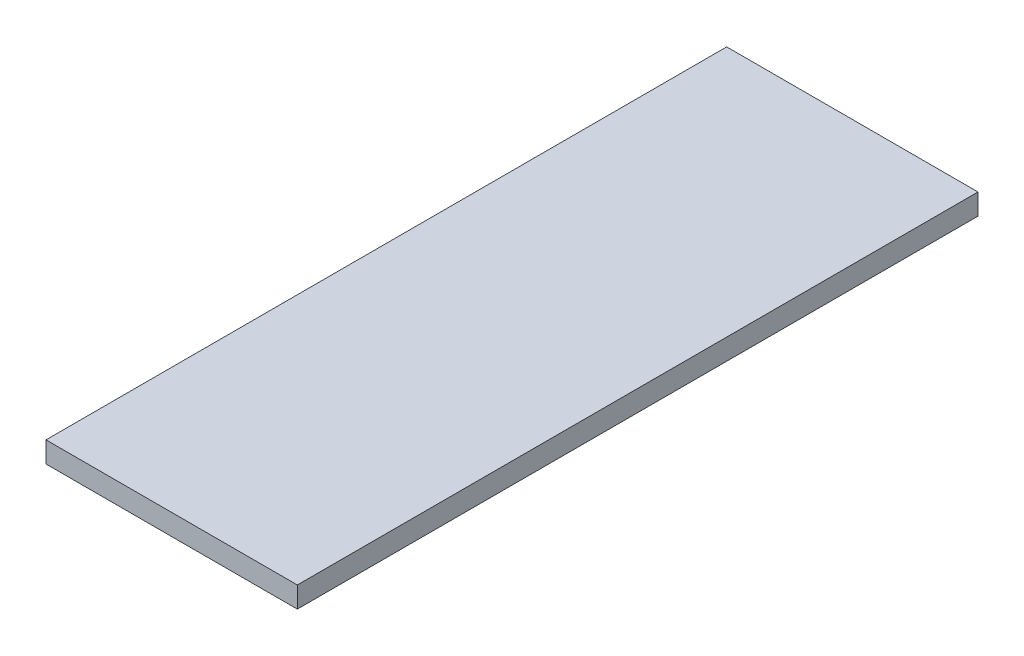
SolidWorks part; units mm, degrees
material "橡木"
ref_plane "前视基准面" through (0, 0, 0) normal (0, 0, 1) x (1, 0, 0)
ref_plane "上视基准面" through (0, 0, 0) normal (0, 1, 0) x (1, 0, 0)
ref_plane "右视基准面" through (0, 0, 0) normal (1, 0, 0) x (0, 0, -1)
other "Configuration Table"
sketch "草图1" plane through (0, 0, 0) normal (0, 1, 0) x (1, 0, 0)
  line L1 (0, 0) -> (240, 0)
  line L2 (0, 0) -> (0, 650)
  line L3 (0, 650) -> (240, 650)
  line L4 (240, 0) -> (240, 650)
  dimension "D1" = 240
  dimension "D2" = 650
extrude "凸台-拉伸1" add sketch "草图1" along normal blind 20
